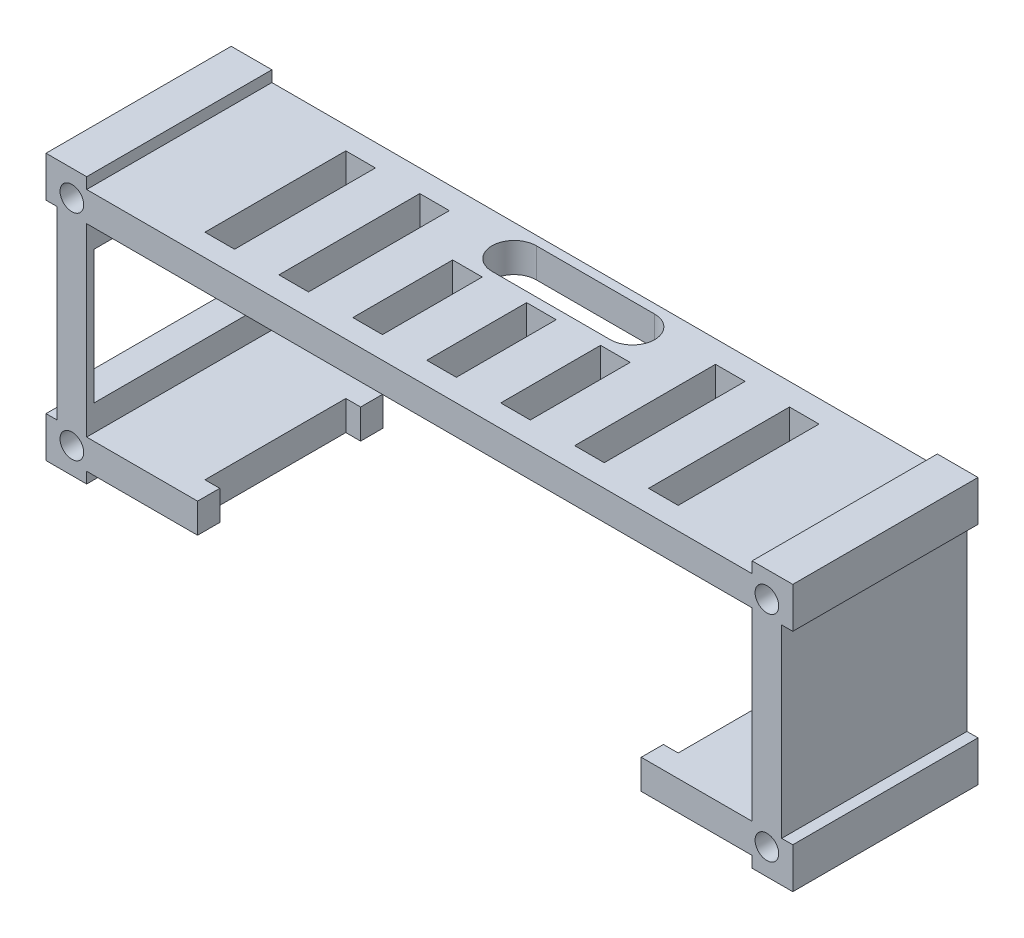
SolidWorks part; units mm, degrees
ref_plane "前视基准面" through (0, 0, 0) normal (0, 0, 1) x (1, 0, 0)
ref_plane "上视基准面" through (0, 0, 0) normal (0, 1, 0) x (1, 0, 0)
ref_plane "右视基准面" through (0, 0, 0) normal (1, 0, 0) x (0, 0, -1)
other "Configuration Table"
sketch3d "3D草图1"
  point P0 (0, 0, -25.05)
  point P1 (10, 0, -25.05)
  point P2 (0, 10, -25.05)
ref_plane "基准面1" through (0, 0, -25.05) normal (0, 0, 1) x (1, 0, 0)
sketch "草图1" plane through (0, 0, -25.05) normal (0, 0, 1) x (1, 0, 0)
  line L0 (-49, -16.5) -> (49, -16.5)
  line L1 (49, -16.5) -> (49, 16.5)
  line L2 (49, 16.5) -> (-49, 16.5)
  line L3 (-49, 16.5) -> (-49, -16.5)
  line L4 (-45, -12.5) -> (45, -12.5)
  line L5 (45, -12.5) -> (45, 12.5)
  line L6 (45, 12.5) -> (-45, 12.5)
  line L7 (-45, 12.5) -> (-45, -12.5)
extrude "凸台-拉伸1" add sketch "草图1" along normal blind 25.05
sketch3d "3D草图2"
  point P0 (0, 0, -25.05)
  point P1 (10, 0, -25.05)
  point P2 (0, 10, -25.05)
ref_plane "基准面2" through (0, 0, -25.05) normal (0, 0, 1) x (1, 0, 0)
sketch "草图2" plane through (0, 0, -25.05) normal (0, 0, 1) x (1, 0, 0)
  line L0 (45, 12.5) -> (50.5, 12.5)
  line L1 (50.5, 12.5) -> (50.5, 18)
  line L2 (50.5, 18) -> (45, 18)
  line L3 (45, 18) -> (45, 12.5)
extrude "凸台-拉伸2" add sketch "草图2" along normal blind 25.05
sketch3d "3D草图3"
  point P0 (0, 0, -25.05)
  point P1 (10, 0, -25.05)
  point P2 (0, 10, -25.05)
ref_plane "基准面3" through (0, 0, -25.05) normal (0, 0, 1) x (1, 0, 0)
sketch "草图3" plane through (0, 0, -25.05) normal (0, 0, 1) x (1, 0, 0)
  line L0 (45, -18) -> (50.5, -18)
  line L1 (50.5, -18) -> (50.5, -12.5)
  line L2 (50.5, -12.5) -> (45, -12.5)
  line L3 (45, -12.5) -> (45, -18)
extrude "凸台-拉伸3" add sketch "草图3" along normal blind 25.05
sketch3d "3D草图4"
  point P0 (0, 0, -25.05)
  point P1 (10, 0, -25.05)
  point P2 (0, 10, -25.05)
ref_plane "基准面4" through (0, 0, -25.05) normal (0, 0, 1) x (1, 0, 0)
sketch "草图4" plane through (0, 0, -25.05) normal (0, 0, 1) x (1, 0, 0)
  line L0 (-50.5, 12.5) -> (-45, 12.5)
  line L1 (-45, 12.5) -> (-45, 18)
  line L2 (-45, 18) -> (-50.5, 18)
  line L3 (-50.5, 18) -> (-50.5, 12.5)
extrude "凸台-拉伸4" add sketch "草图4" along normal blind 25.05
sketch3d "3D草图5"
  point P0 (0, 0, -25.05)
  point P1 (10, 0, -25.05)
  point P2 (0, 10, -25.05)
ref_plane "基准面5" through (0, 0, -25.05) normal (0, 0, 1) x (1, 0, 0)
sketch "草图5" plane through (0, 0, -25.05) normal (0, 0, 1) x (1, 0, 0)
  line L0 (-50.5, -18) -> (-45, -18)
  line L1 (-45, -18) -> (-45, -12.5)
  line L2 (-45, -12.5) -> (-50.5, -12.5)
  line L3 (-50.5, -12.5) -> (-50.5, -18)
extrude "凸台-拉伸5" add sketch "草图5" along normal blind 25.05
sketch3d "3D草图6"
  point P0 (0, 0, -25.05)
  point P1 (10, 0, -25.05)
  point P2 (0, 10, -25.05)
ref_plane "基准面6" through (0, 0, -25.05) normal (0, 0, 1) x (1, 0, 0)
sketch "草图6" plane through (0, 0, -25.05) normal (0, 0, 1) x (1, 0, 0)
  circle A0 centre (-47, -14.5) radius 1.6
  circle A1 centre (-47, 14.5) radius 1.6
  circle A2 centre (47, -14.5) radius 1.6
  circle A3 centre (47, 14.5) radius 1.6
extrude "切除-拉伸1" cut sketch "草图6" along normal blind 25.05
sketch3d "3D草图7"
  point P0 (0, -16.5, 0)
  point P1 (10, -16.5, 0)
  point P2 (0, -16.5, -10)
ref_plane "基准面7" through (0, -16.5, 0) normal (0, 1, 0) x (1, 0, 0)
sketch "草图7" plane through (0, -16.5, 0) normal (0, 1, 0) x (1, 0, 0)
  line L0 (-32, 22.05) -> (-28, 22.05)
  line L1 (-28, 22.05) -> (-28, 3)
  line L2 (-28, 3) -> (-32, 3)
  line L3 (-32, 3) -> (-32, 22.05)
  line L4 (-22, 22.05) -> (-18, 22.05)
  line L5 (-18, 22.05) -> (-18, 3)
  line L6 (-18, 3) -> (-22, 3)
  line L7 (-22, 3) -> (-22, 22.05)
  line L8 (-12, 22.05) -> (-8, 22.05)
  line L9 (-8, 22.05) -> (-8, 3)
  line L10 (-8, 3) -> (-12, 3)
  line L11 (-12, 3) -> (-12, 22.05)
  line L12 (-2, 22.05) -> (2, 22.05)
  line L13 (2, 22.05) -> (2, 3)
  line L14 (2, 3) -> (-2, 3)
  line L15 (-2, 3) -> (-2, 22.05)
  line L16 (8, 22.05) -> (12, 22.05)
  line L17 (12, 22.05) -> (12, 3)
  line L18 (12, 3) -> (8, 3)
  line L19 (8, 3) -> (8, 22.05)
  line L20 (18, 22.05) -> (22, 22.05)
  line L21 (22, 22.05) -> (22, 3)
  line L22 (22, 3) -> (18, 3)
  line L23 (18, 3) -> (18, 22.05)
  line L24 (28, 22.05) -> (32, 22.05)
  line L25 (32, 22.05) -> (32, 3)
  line L26 (32, 3) -> (28, 3)
  line L27 (28, 3) -> (28, 22.05)
extrude "切除-拉伸2" cut sketch "草图7" along normal blind 4
sketch3d "3D草图8"
  point P0 (0, 12.5, 0)
  point P1 (10, 12.5, 0)
  point P2 (0, 12.5, -10)
ref_plane "基准面8" through (0, 12.5, 0) normal (0, 1, 0) x (1, 0, 0)
sketch "草图8" plane through (0, 12.5, 0) normal (0, 1, 0) x (1, 0, 0)
  line L0 (-32, 22.05) -> (-28, 22.05)
  line L1 (-28, 22.05) -> (-28, 3)
  line L2 (-28, 3) -> (-32, 3)
  line L3 (-32, 3) -> (-32, 22.05)
  line L4 (-22, 22.05) -> (-18, 22.05)
  line L5 (-18, 22.05) -> (-18, 3)
  line L6 (-18, 3) -> (-22, 3)
  line L7 (-22, 3) -> (-22, 22.05)
  line L8 (-12, 16.5) -> (-8, 16.5)
  line L9 (-8, 16.5) -> (-8, 3)
  line L10 (-8, 3) -> (-12, 3)
  line L11 (-12, 3) -> (-12, 16.5)
  line L12 (-2, 16.5) -> (2, 16.5)
  line L13 (2, 16.5) -> (2, 3)
  line L14 (2, 3) -> (-2, 3)
  line L15 (-2, 3) -> (-2, 16.5)
  line L16 (8, 16.5) -> (12, 16.5)
  line L17 (12, 16.5) -> (12, 3)
  line L18 (12, 3) -> (8, 3)
  line L19 (8, 3) -> (8, 16.5)
  line L20 (18, 22.05) -> (22, 22.05)
  line L21 (22, 22.05) -> (22, 3)
  line L22 (22, 3) -> (18, 3)
  line L23 (18, 3) -> (18, 22.05)
  line L24 (28, 22.05) -> (32, 22.05)
  line L25 (32, 22.05) -> (32, 3)
  line L26 (32, 3) -> (28, 3)
  line L27 (28, 3) -> (28, 22.05)
extrude "切除-拉伸3" cut sketch "草图8" along normal blind 4
sketch3d "3D草图9"
  point P0 (-49, 0, 0)
  point P1 (-49, 0, -10)
  point P2 (-49, 10, 0)
ref_plane "基准面9" through (-49, 0, 0) normal (1, 0, 0) x (0, 0, -1)
sketch "草图9" plane through (-49, 0, 0) normal (1, 0, 0) x (0, 0, -1)
  line L0 (24.05, -9) -> (24.05, 9)
  line L1 (24.05, 9) -> (1, 9)
  line L2 (1, 9) -> (1, -9)
  line L3 (1, -9) -> (24.05, -9)
extrude "切除-拉伸4" cut sketch "草图9" along normal blind 4
sketch3d "3D草图10"
  point P0 (0, 0, -25.05)
  point P1 (10, 0, -25.05)
  point P2 (0, 10, -25.05)
ref_plane "基准面10" through (0, 0, -25.05) normal (0, 0, 1) x (1, 0, 0)
sketch "草图10" plane through (0, 0, -25.05) normal (0, 0, 1) x (1, 0, 0)
  line L0 (-30, -17) -> (30, -17)
  line L1 (30, -17) -> (30, -12.5)
  line L2 (30, -12.5) -> (-30, -12.5)
  line L3 (-30, -12.5) -> (-30, -17)
extrude "切除-拉伸5" cut sketch "草图10" along normal blind 25.05
sketch3d "3D草图11"
  point P0 (0, 12.5, 0)
  point P1 (10, 12.5, 0)
  point P2 (0, 12.5, -10)
ref_plane "基准面11" through (0, 12.5, 0) normal (0, 1, 0) x (1, 0, 0)
sketch "草图11" plane through (0, 12.5, 0) normal (0, 1, 0) x (1, 0, 0)
  line L0 (-8, 17.82) -> (8, 17.82)
  line L1 (8, 23.82) -> (-8, 23.82)
  arc A0 (8, 17.82) -> (8, 23.82) centre (8, 20.82) ccw
  arc A1 (-8, 23.82) -> (-8, 17.82) centre (-8, 20.82) ccw
extrude "切除-拉伸6" cut sketch "草图11" along normal blind 4
